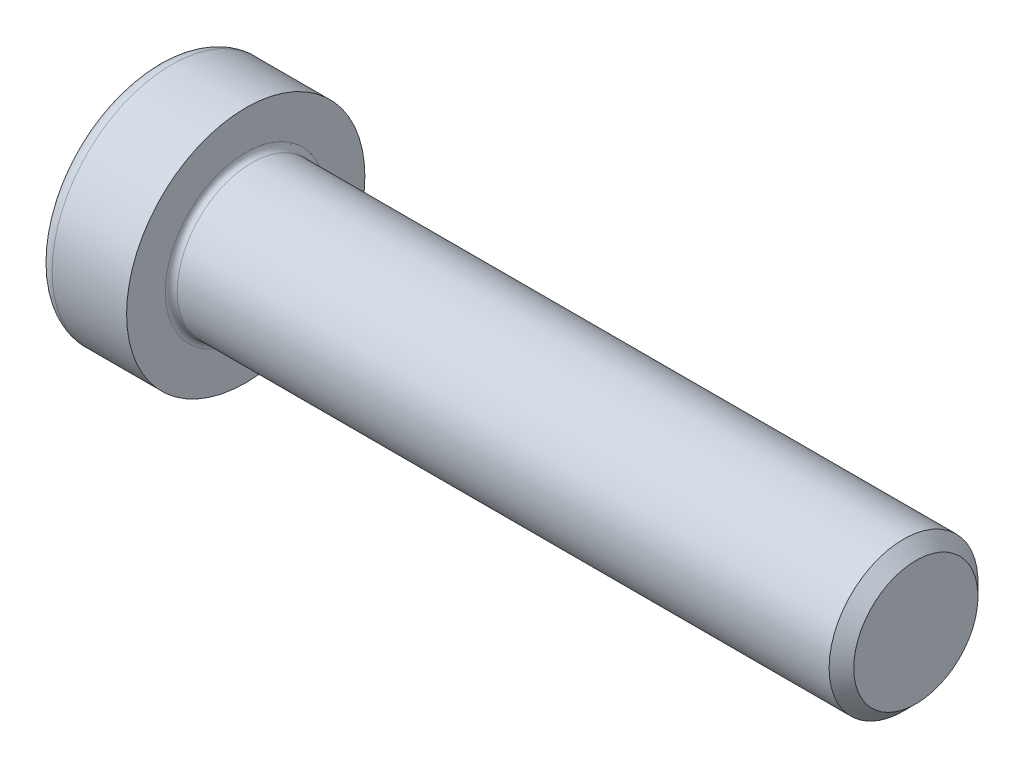
SolidWorks part; units mm, degrees
revolve "Base-Revolve" add sketch "BodySke"
sketch "BodySke" plane through (0, 0, 0) normal (0, 0, 1) x (1, 0, 0)
  line L0 (0, 0) -> (0, 8)
  line L1 (0, 8) -> (6, 8)
  line L2 (6, 8) -> (6, 5)
  line L3 (6, 5) -> (50.172, 5)
  line L4 (51, 4.172) -> (51, 0)
  line L5 (51, 0) -> (0, 0)
  line L6 (-31.75, 0) -> (127, 0) construction
  line L8 (51, 4.172) -> (50.172, 5)
  line L10 (51, -4.172) -> (50.172, -5) construction
  line L11 (7.5, 4.525) -> (7.5, -1.825) construction
  line L12 (25, 4.525) -> (25, -1.825) construction
  line L13 (-9, 4.525) -> (-9, -1.825) construction
  dimension "Head_ht" = 6
  dimension "Length" = 45
  dimension "Body_ch_ang" = 45
  dimension "Diameter" = 10
  dimension "Minor_dia" = 8.344
  dimension "Advance" = 1.5
  dimension "Thread_nom" = 26
  dimension "Thread_length" = 60
  dimension "Head_dia" = 16
cosmetic thread "ThreadCosmetic"
fillet "Fillet1" radius 0.4 1 edges at (6, 0, 5)
fillet "Fillet2" radius 1 1 edges at (0, 0, 8)
material "AISI 316 Нержавеющая сталь, лист (SS)"
ref_plane "Plane1" through (0, 0, 0) normal (0, 0, 1) x (1, 0, 0)
ref_plane "Plane2" through (0, 0, 0) normal (0, 1, 0) x (1, 0, 0)
ref_plane "Plane3" through (0, 0, 0) normal (1, 0, 0) x (0, 0, -1)
other "Configuration Table"
sketch "Sketch2" plane through (0, 0, 0) normal (0, 0, 1) x (1, 0, 0)
  line L0 (0, 3.5) -> (4.5, 3.5)
  line L1 (4.5, 3.5) -> (6.5207, 0)
  line L2 (-31.75, 0) -> (127, 0) construction
  line L3 (6.5207, 0) -> (0, 0)
  line L4 (0, 0) -> (0, 3.5)
  line L6 (0, 0) -> (47.625, 0) construction
  dimension "D1" = 3.5
  dimension "D2" = 60
  dimension "Depth" = 4.5
revolve "Hex-PreBroach" cut sketch "Sketch2" angle 360 about L6
sketch "Sketch3" plane through (0, 0, 0) normal (-1, 0, 0) x (0, 0.5, 0.866)
  line L0 (2.0207, 3.5) -> (-2.0207, 3.5)
  line L1 (-2.0207, 3.5) -> (-4.0415, 0)
  line L2 (2.0207, 3.5) -> (4.0415, 0)
  line L3 (2.0207, -3.5) -> (4.0415, 0)
  line L4 (2.0207, -3.5) -> (-2.0207, -3.5)
  line L5 (-2.0207, -3.5) -> (-4.0415, 0)
  dimension "D1" = 3.5
  dimension "D2" = 3.5
  dimension "Hex_size" = 7
extrude "Hex" cut sketch "Sketch3" against normal blind 4.5
sketch "ThdSchSke" plane through (0, 0, 0) normal (0, 0, 1) x (1, 0, 0)
  line L0 (25, -4.172) -> (24.4202, -5)
  line L1 (25, -4.172) -> (25.5798, -5)
  line L2 (25.5798, -5) -> (25.5798, -6.25)
  line L3 (-3.175, 0) -> (5.1513, 0) construction
  line L4 (0, 7) -> (0, -7) construction
  line L5 (25.5798, -6.25) -> (24.4202, -6.25)
  line L6 (24.4202, -6.25) -> (24.4202, -5)
  dimension "Thread_minor" = 8.344
  dimension "Diameter" = 10
  dimension "Start" = 25
revolve "ThreadSchematic" [suppressed] cut sketch "ThdSchSke" angle 360 about L3
pattern_linear "ThdSchPat" [suppressed]
equation "\"D2@Sketch3\" = \"Hex_size@Sketch3\" / 2"
equation "\"D1@Sketch3\" = \"Hex_size@Sketch3\" / 2"
equation "\"D1@Sketch2\" = \"Hex_size@Sketch3\" / 2"
equation "\"Thread_minor@ThreadCosmetic\"  =  \"Minor_dia@BodySke\""
equation "\"Depth@Sketch2\" =  \"Key_eng@Hex\""
equation "\"Thread_length@ThreadCosmetic\" = ((sgn( (\"Length@BodySke\" - \"Advance@BodySke\" * 3.0) - \"Thread_nom@BodySke\" )-1)*( (\"Length@BodySke\" - \"Advance@BodySke\" * 3.0) - \"Thread_nom@BodySke\" ))/-2+ \"Thread_nom@BodySke\""
equation "\"Thread_minor@ThdSchSke\" = \"Minor_dia@BodySke\""
equation "\"Diameter@ThdSchSke\" = \"Diameter@BodySke\""
equation "\"Overcut@ThdSchSke\" = \"Diameter@BodySke\" * 1.25"
equation "\"Start@ThdSchSke\" = \"Head_ht@BodySke\" + \"Length@BodySke\" - \"Thread_length@ThreadCosmetic\"  '---Non-countersunk---"
equation "\"Num_threads@ThdSchPat\" = int( \"Thread_length@ThreadCosmetic\" / \"Advance@BodySke\" + 0.999 )  + 1"
equation "\"Advance@ThdSchPat\" = \"Thread_length@ThreadCosmetic\" /  (\"Num_threads@ThdSchPat\" - 1) 'relax it"
equation "\"Num_threads@ThdSchPat\" = \"Num_threads@ThdSchPat\" - sgn( \"Num_threads@ThdSchPat\" - 1) '---chamfered tips only---"
